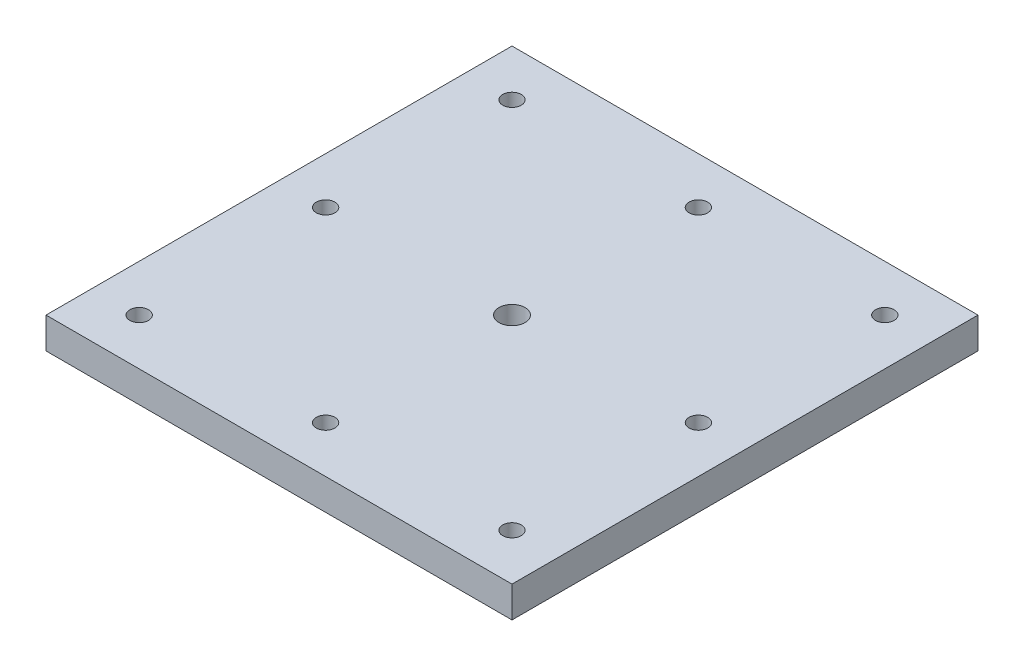
SolidWorks part; units mm, degrees
ref_plane "Alzado" through (0, 0, 0) normal (0, 0, 1) x (1, 0, 0)
ref_plane "Planta" through (0, 0, 0) normal (0, 1, 0) x (1, 0, 0)
ref_plane "Vista lateral" through (0, 0, 0) normal (1, 0, 0) x (0, 0, -1)
sketch "Croquis1" plane through (0, 0, 0) normal (0, 1, 0) x (1, 0, 0)
  line L1 (-30, 30) -> (30, 30) construction
  line L2 (-30, 30) -> (-30, -30) construction
  line L3 (-30, -30) -> (30, -30) construction
  line L4 (30, 30) -> (30, -30) construction
  line L5 (-30, 30) -> (30, -30) construction
  line L6 (-30, -30) -> (30, 30) construction
  line L7 (-37.5, 37.5) -> (37.5, 37.5)
  line L8 (-37.5, 37.5) -> (-37.5, -37.5)
  line L9 (-37.5, -37.5) -> (37.5, -37.5)
  line L10 (37.5, 37.5) -> (37.5, -37.5)
  line L11 (-37.5, 37.5) -> (37.5, -37.5) construction
  line L12 (-37.5, -37.5) -> (37.5, 37.5) construction
  circle A0 centre (30, 0) radius 1.5
  circle A1 centre (30, 30) radius 1.5
  circle A2 centre (0, 30) radius 1.5
  circle A3 centre (-30, 30) radius 1.5
  circle A4 centre (-30, 0) radius 1.5
  circle A5 centre (-30, -30) radius 1.5
  circle A6 centre (0, -30) radius 1.5
  circle A7 centre (30, -30) radius 1.5
  circle A8 centre (0, 0) radius 2.1
  point P0 (0, 0)
  point P5 (0, 0)
  dimension "D3" = 3
  dimension "D4" = 4.2
  dimension "D1" = 60
  dimension "D2" = 75
extrude "Saliente-Extruir1" add sketch "Croquis1" along normal blind 5
